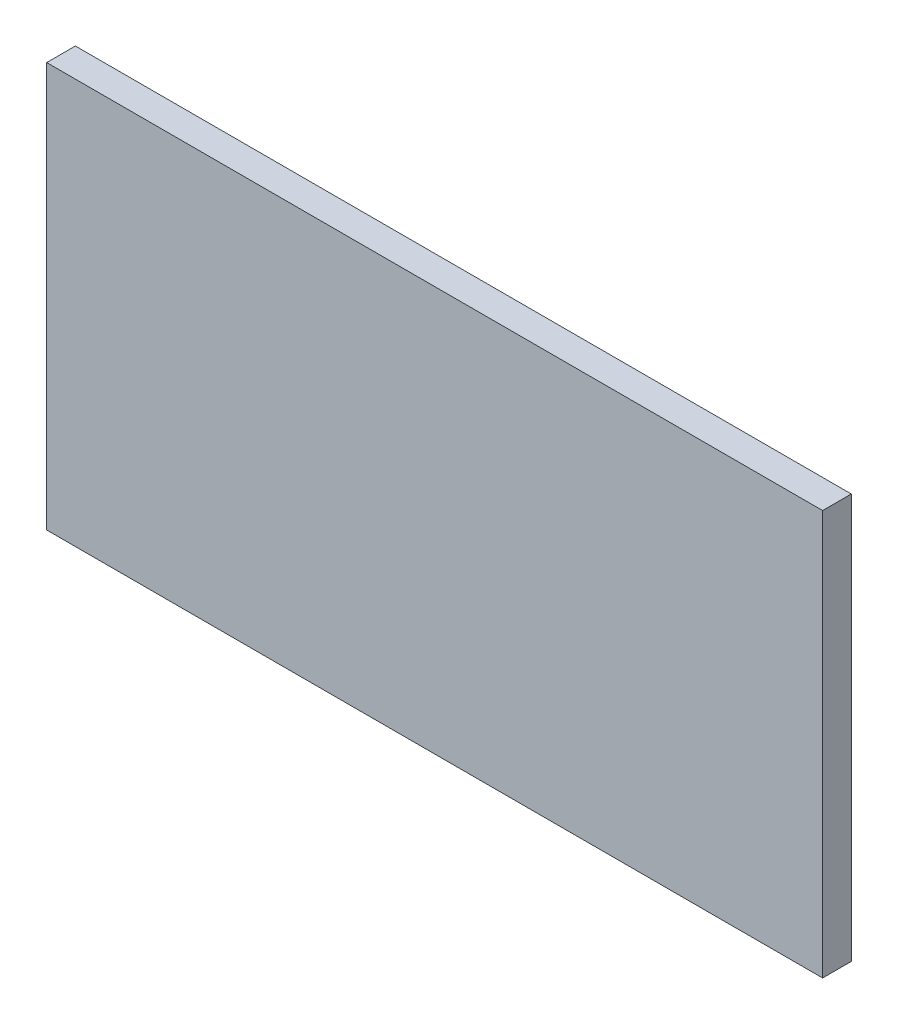
SolidWorks part; units mm, degrees
ref_plane "前视基准面" through (0, 0, 0) normal (0, 0, 1) x (1, 0, 0)
ref_plane "上视基准面" through (0, 0, 0) normal (0, 1, 0) x (1, 0, 0)
ref_plane "右视基准面" through (0, 0, 0) normal (1, 0, 0) x (0, 0, -1)
other "Configuration Table"
sketch "草图1" plane through (0, 0, 0) normal (0, 0, 1) x (1, 0, 0)
  line L0 (0, 0) -> (46, 0)
  line L1 (46, 0) -> (46, 24)
  line L2 (46, 24) -> (0, 24)
  line L3 (0, 24) -> (0, 0)
  dimension "width" = 46
  dimension "height" = 24
extrude "BlockExtrude" add sketch "草图1" along normal blind 1.7
